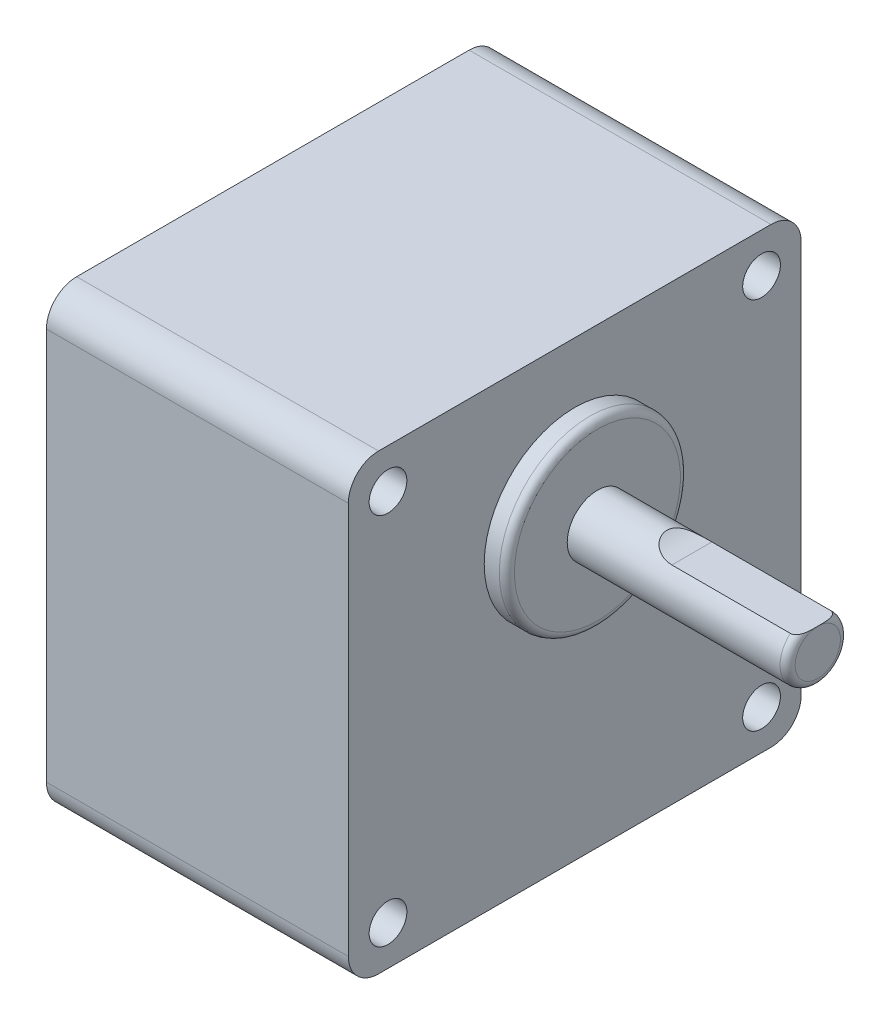
SolidWorks part; units mm, degrees
ref_plane "Front Plane" through (0, 0, 0) normal (0, 0, 1) x (1, 0, 0)
ref_plane "Top Plane" through (0, 0, 0) normal (0, 1, 0) x (1, 0, 0)
ref_plane "Right Plane" through (0, 0, 0) normal (1, 0, 0) x (0, 0, -1)
ref_plane "Plane1" through (-3, 0, 0) normal (1, 0, 0) x (0, 0, -1)
sketch "Sketch1" plane through (-3, 0, 0) normal (1, 0, 0) x (0, 0, -1)
  line L0 (0, 20) -> (0, -40) construction
  line L1 (-30, 20) -> (30, 20)
  line L2 (-30, 20) -> (-30, -40)
  line L3 (-30, -40) -> (30, -40)
  line L4 (30, 20) -> (30, -40)
  line L5 (-30, -10) -> (30, -10) construction
  point P10 (0, -10)
  dimension "FIX_2" = 60
  dimension "FIX_3" = 10
extrude "Boss-Extrude1" add sketch "Sketch1" against normal blind 40
sketch "Sketch2" plane through (-3, 0, 0) normal (1, 0, 0) x (0, 0, -1)
  line L1 (0, 20) -> (0, -40) construction
  circle A0 centre (0, -10) radius 35 construction
  circle A1 centre (-24.7475, 14.75) radius 2.5
  circle A2 centre (24.7475, 14.75) radius 2.5
  circle A3 centre (24.7475, -34.75) radius 2.5
  circle A4 centre (-24.7475, -34.75) radius 2.5
  dimension "FIX_5" = 70
  dimension "FIX_6" = 5
  dimension "FIX_7" = 49.5
extrude "Cut-Extrude1" cut sketch "Sketch2" against normal through all
fillet "Fillet1" radius 4 4 edges at (-23, -40, -30) (-23, -40, 30) (-23, 20, 30) (-23, 20, -30)
sketch "Sketch3" plane through (0, 0, 0) normal (0, 0, 1) x (1, 0, 0)
  line L0 (-3, 0) -> (29.2, 0) construction
  line L1 (-3, 20) -> (-3, -40) construction
  line L2 (-3, 12) -> (0, 12)
  line L3 (0, 12) -> (0, 4)
  line L4 (0, 4) -> (29.2, 4)
  line L5 (29.2, 4) -> (29.2, 0)
  line L6 (29.2, 0) -> (-3, 0)
  line L7 (-3, 0) -> (-3, 12)
  dimension "FIX_10" = 24
  dimension "FIX_11" = 8
  dimension "FIX_9" = 32.2
revolve "Revolve1" add sketch "Sketch3" angle 360 about L0
fillet "Fillet2" radius 1 2 edges at (29.2, 0, 4) (0, 0, 12)
sketch "Sketch4" plane through (0, 0, 0) normal (0, 0, 1) x (1, 0, 0)
  line L0 (29.2, 4) -> (9.2, 4)
  line L1 (0, 4) -> (29.2, 4) construction
  line L2 (29.2, 4) -> (29.2, 3)
  line L4 (29.2, 3) -> (12.5166, 3)
  arc A0 (9.2, 4) -> (12.5166, 3) centre (12.5166, 9) ccw
  dimension "FIX_14" = 6
  dimension "FIX_15" = 1
  dimension "FIX_16" = 20
extrude "Cut-Extrude2" cut sketch "Sketch4" against normal through all and the other way through all
sketch "Sketch5" plane through (0, 0, 0) normal (0, 0, 1) x (1, 0, 0)
  line L0 (-40.5, -10) -> (-43, -10) construction
  line L1 (-40.5, -10) -> (-40.5, 17)
  line L2 (-40.5, 17) -> (-43, 17)
  line L3 (-43, 17) -> (-43, -10)
  line L6 (-40.5, -10) -> (-43, -10)
  dimension "FIX_17" = 2.5
  dimension "FIX_18" = 40
  dimension "FIX_19" = 54
revolve "Cut-Revolve1" cut sketch "Sketch5" angle 360 about L0
